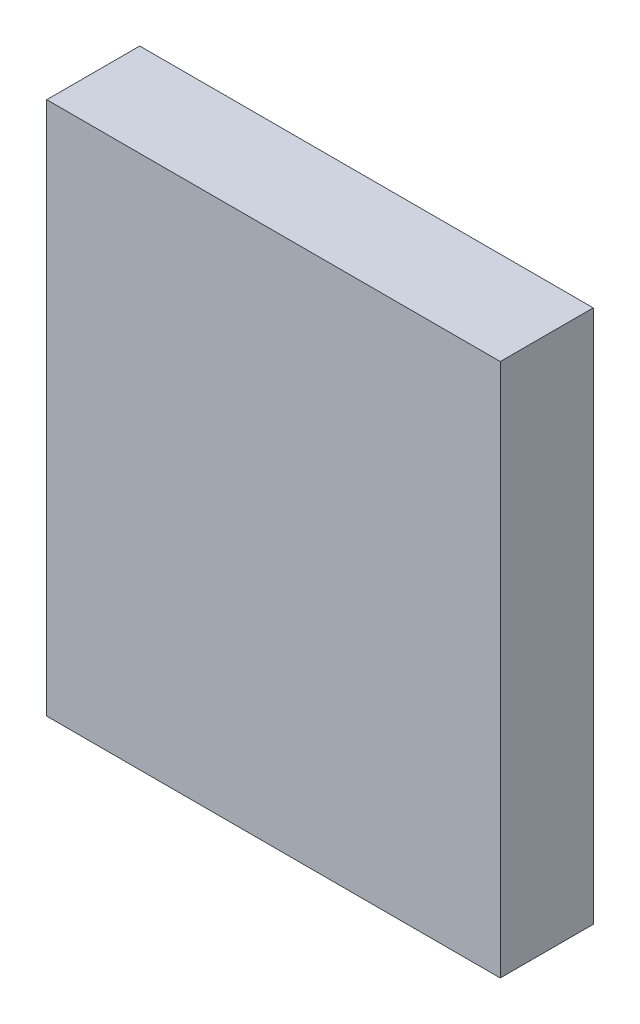
SolidWorks part; units mm, degrees
ref_plane "Front Plane" through (0, 0, 0) normal (0, 0, 1) x (1, 0, 0)
ref_plane "Top Plane" through (0, 0, 0) normal (0, 1, 0) x (1, 0, 0)
ref_plane "Right Plane" through (0, 0, 0) normal (1, 0, 0) x (0, 0, -1)
sketch "Sketch1" plane through (0, 0, 0) normal (0, 0, 1) x (1, 0, 0)
  line L0 (-2.4382, 2.8702) -> (2.4382, 2.8702)
  line L1 (2.4382, 2.8702) -> (2.4382, -2.8702)
  line L2 (2.4382, -2.8702) -> (-2.4382, -2.8702)
  line L3 (-2.4382, -2.8702) -> (-2.4382, 2.8702)
extrude "Component_Outline" add sketch "Sketch1" along normal blind 1 separate body
sketch3d "3DSketch1"
  line L0 (0, 0, 0) -> (1, 0, 0)
  line L1 (0, 0, 0) -> (0, 1, 0)
  line L2 (0, 0, 0) -> (0, 0, 1)
  point P0 (0, 0, 0)
